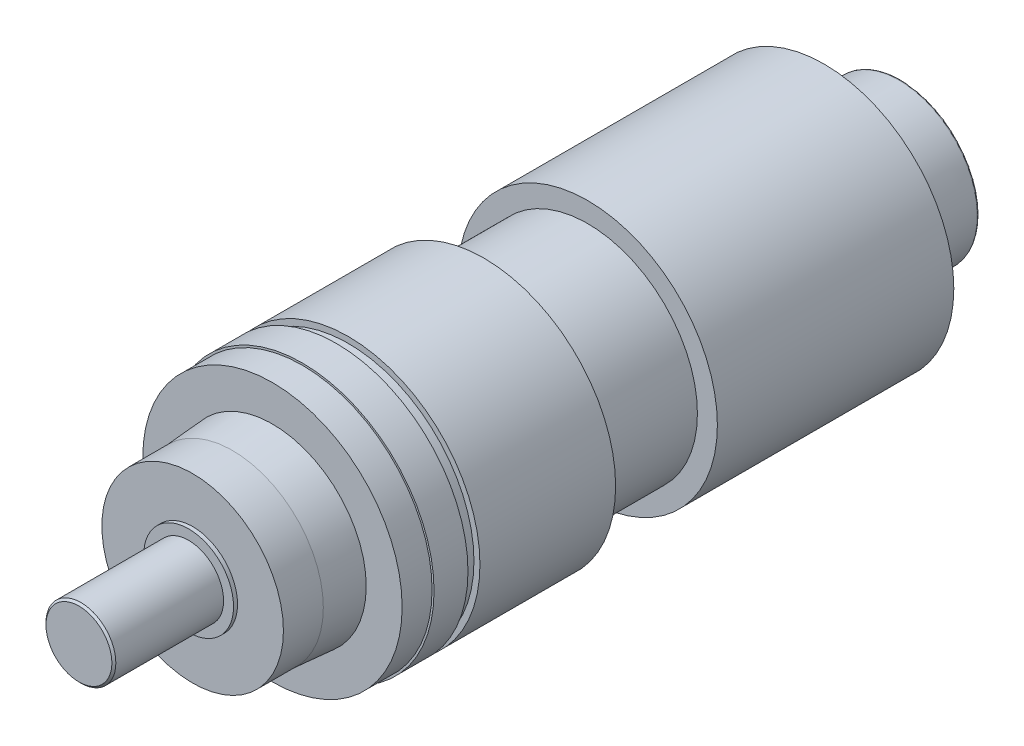
SolidWorks part; units mm, degrees
ref_plane "Front" through (0, 0, 0) normal (0, 0, 1) x (1, 0, 0)
ref_plane "Top" through (0, 0, 0) normal (0, 1, 0) x (1, 0, 0)
ref_plane "Right" through (0, 0, 0) normal (1, 0, 0) x (0, 0, -1)
sketch "Sketch1" plane through (0, 0, 0) normal (1, 0, 0) x (0, 0, -1)
  line L0 (-61.708, 0) -> (368.538, 0) construction
  line L1 (-55, 0) -> (358, 0)
  line L3 (0, -8.3759) -> (0, 32.5634) construction
  line L4 (358, 30.75) -> (358, 0)
  line L13 (356.8, 39.15) -> (331.5, 40.0335)
  line L14 (331.5, 42.5) -> (318.5, 42.5)
  line L15 (331.5, 40.0335) -> (331.5, 42.5)
  line L16 (318.5, 65) -> (200.0029, 65)
  line L17 (200.0029, 65) -> (200.0029, 55)
  line L18 (200.0029, 55) -> (148, 55)
  line L19 (148, 55) -> (148, 66)
  line L20 (148, 66) -> (80, 66)
  line L21 (74, 66) -> (57, 66)
  line L23 (80, 66) -> (80, 63)
  line L24 (74, 63) -> (74, 66)
  line L31 (57, 66) -> (57, 65)
  line L32 (42, 47) -> (42, 65)
  line L34 (2, 45.5) -> (2, 22.5)
  line L35 (0, 22.5) -> (0, 17.5)
  line L36 (-55, 17.5) -> (-55, 0)
  line L37 (-55, 17.5) -> (0, 17.5)
  line L38 (0, 22.5) -> (2, 22.5)
  line L39 (2, 45.5) -> (22, 45.5)
  line L40 (22, 45.5) -> (42, 47)
  line L41 (42, 65) -> (57, 65)
  line L42 (74, 63) -> (80, 63)
  line L43 (318.5, 65) -> (318.5, 42.5)
  arc A2 (358, 30.75) -> (356.8, 39.15) centre (328, 30.75) ccw
  dimension "D23" = 30
  dimension "D24" = 78.3
  dimension "D1" = 35
  dimension "D2" = 55
  dimension "D3" = 2
  dimension "D4" = 45
  dimension "D5" = 91
  dimension "D6" = 22
  dimension "D7" = 94
  dimension "D8" = 42
  dimension "D9" = 130
  dimension "D10" = 57
  dimension "D11" = 132
  dimension "D12" = 126
  dimension "D13" = 74
  dimension "D14" = 80
  dimension "D15" = 148
  dimension "D16" = 110
  dimension "D17" = 130
  dimension "D18" = 200.0029
  dimension "D19" = 318.5
  dimension "D20" = 358
  dimension "D21" = 85
  dimension "D22" = 331.5
  dimension "D25" = 356.8
  dimension "D26" = 2
revolve "Revolve1" add sketch "Sketch1" angle 360 about L0
fillet "Fillet1" radius 1 1 edges at (39.15, 0, -356.8)
chamfer "Chamfer1" distance 1 1 edges at (17.5, 0, 55)
